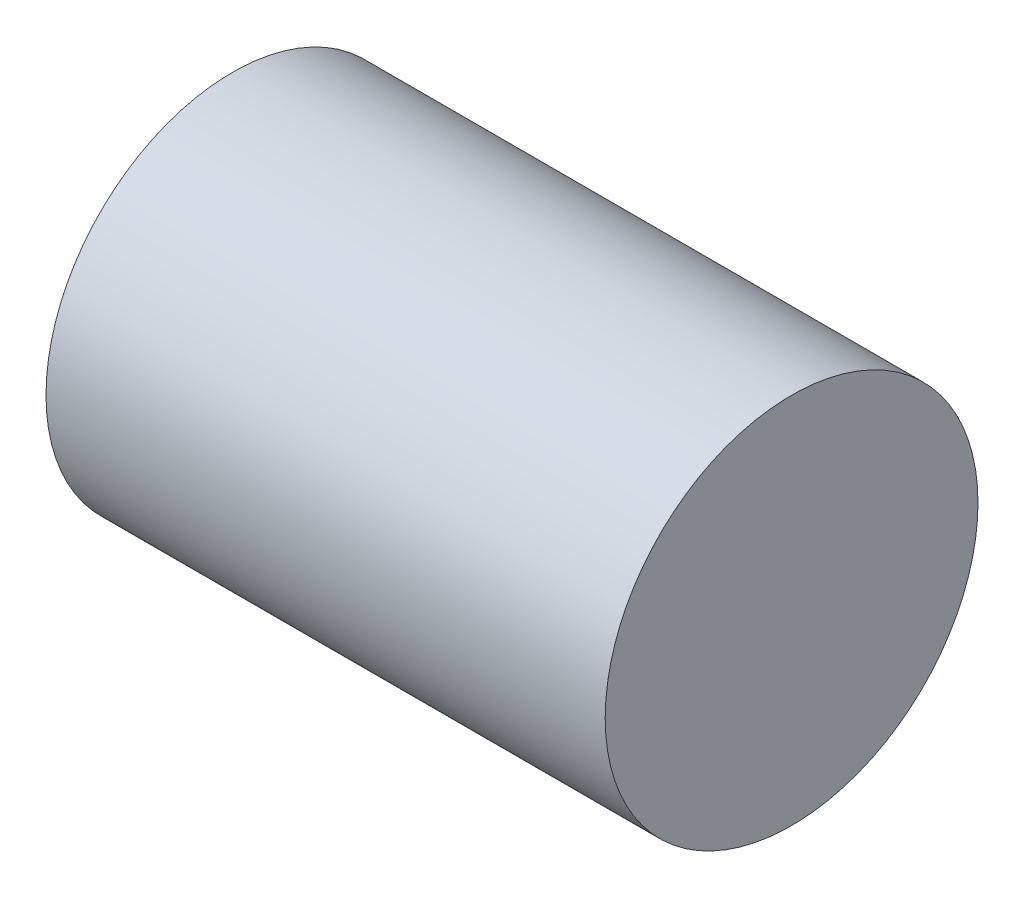
SolidWorks part; units mm, degrees
ref_plane "Front Plane" through (0, 0, 0) normal (0, 0, 1) x (1, 0, 0)
ref_plane "Top Plane" through (0, 0, 0) normal (0, 1, 0) x (1, 0, 0)
ref_plane "Right Plane" through (0, 0, 0) normal (1, 0, 0) x (0, 0, -1)
sketch "Sketch1" plane through (0, 0, 0) normal (0, 0, 1) x (1, 0, 0)
  line L0 (0, 25.4) -> (-25.4, 25.4)
  line L1 (0, 0) -> (-76.2, 0)
  line L2 (0, 0) -> (0, 25.4)
  line L3 (-25.4, 25.4) -> (-76.2, 25.4)
  line L4 (-76.2, 0) -> (-76.2, 25.4)
  line L5 (64.3305, 0) -> (-113.0542, 0) construction
  dimension "D1" = 25.4
  dimension "D2" = 25.4
  dimension "D3" = 50.8
revolve "Revolve1" add sketch "Sketch1" angle 360 about L5
